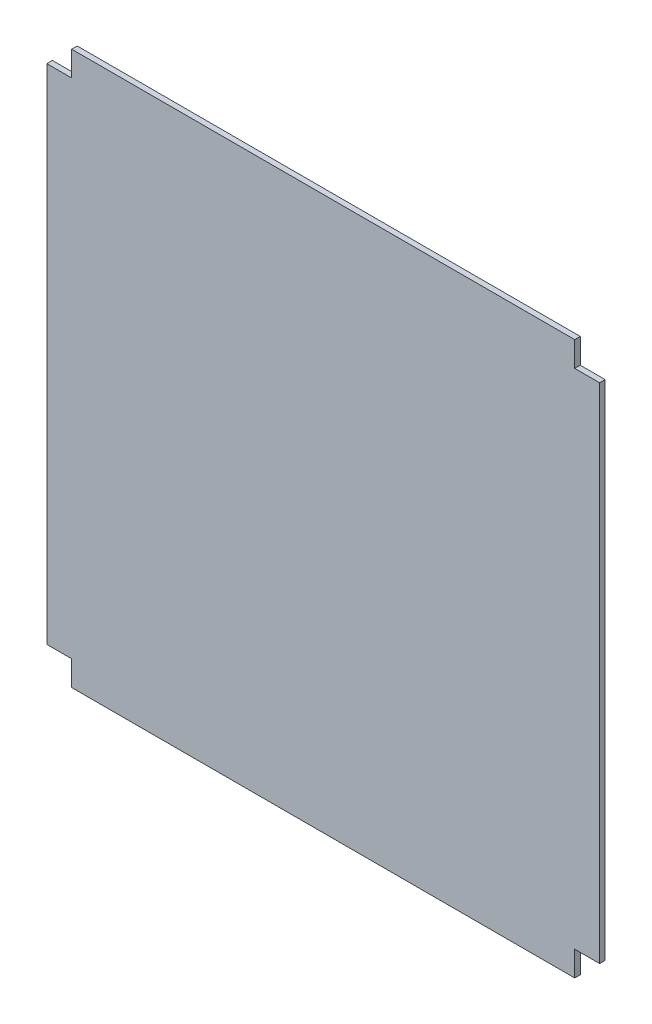
SolidWorks part; units mm, degrees
ref_plane "Front Plane" through (0, 0, 0) normal (0, 0, 1) x (1, 0, 0)
ref_plane "Top Plane" through (0, 0, 0) normal (0, 1, 0) x (1, 0, 0)
ref_plane "Right Plane" through (0, 0, 0) normal (1, 0, 0) x (0, 0, -1)
sketch "Sketch1" plane through (0, 0, 0) normal (0, 0, 1) x (1, 0, 0)
  line L0 (339.8408, -290.7195) -> (339.8408, -267.8595)
  line L1 (339.8408, -267.8595) -> (362.7008, -267.8595)
  line L4 (362.7008, -267.8595) -> (362.7008, 193.4045)
  line L6 (362.7008, 193.4045) -> (339.8408, 193.4045)
  line L7 (339.8408, 193.4045) -> (339.8408, 216.2645)
  line L9 (339.8408, 216.2645) -> (-121.4232, 216.2645)
  line L10 (-121.4232, 216.2645) -> (-121.4232, 193.4045)
  line L11 (-121.4232, 193.4045) -> (-144.2832, 193.4045)
  line L13 (-144.2832, 193.4045) -> (-144.2832, -267.8595)
  line L14 (-144.2832, -267.8595) -> (-121.4232, -267.8595)
  line L15 (-121.4232, -267.8595) -> (-121.4232, -290.7195)
  line L16 (-121.4232, -290.7195) -> (339.8408, -290.7195)
  dimension "D1" = 461.264
  dimension "D2" = 461.264
  dimension "D3" = 461.264
extrude "Boss-Extrude1" add sketch "Sketch1" along normal blind 5.08 contours L9 L10 L11 L13 L14 L15 L16 L0 L1 L4 L6 L7
